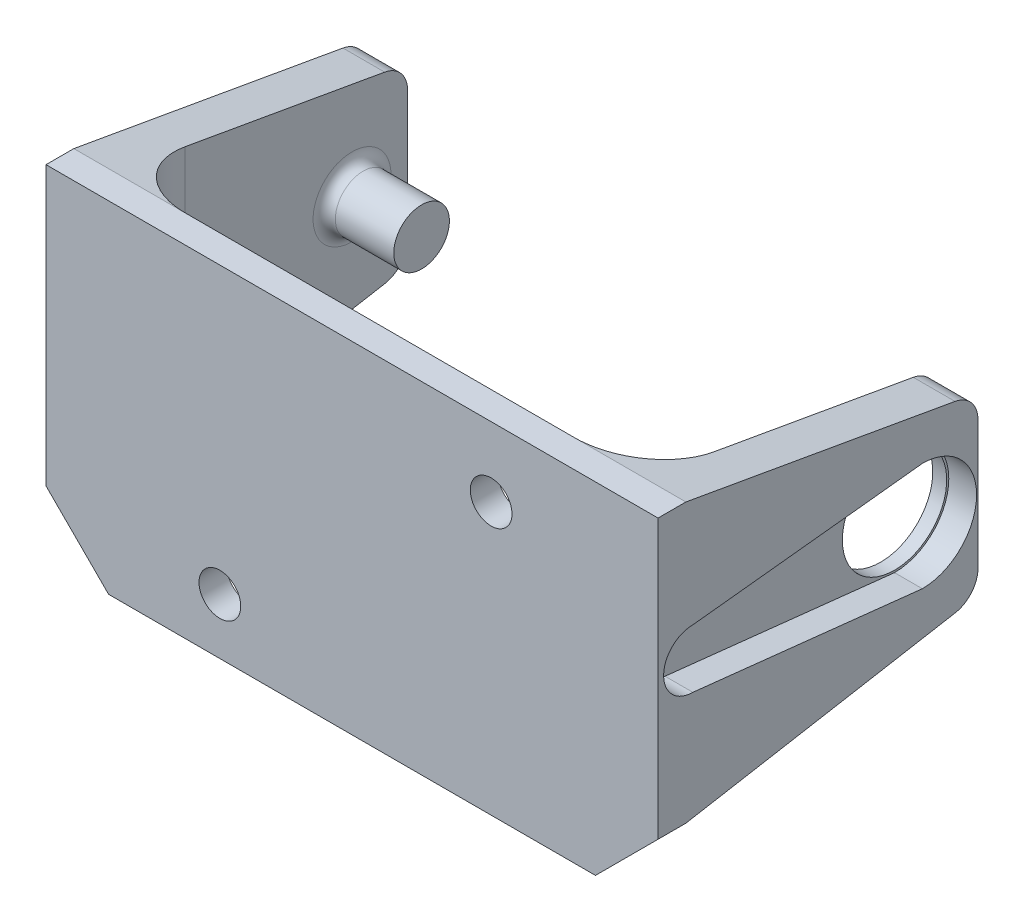
SolidWorks part; units mm, degrees
ref_plane "Front Plane" through (0, 0, 0) normal (0, 0, 1) x (1, 0, 0)
ref_plane "Top Plane" through (0, 0, 0) normal (0, 1, 0) x (1, 0, 0)
ref_plane "Right Plane" through (0, 0, 0) normal (1, 0, 0) x (0, 0, -1)
sketch "Sketch1" plane through (0, 0, 0) normal (0, 0, 1) x (1, 0, 0)
  line L1 (-19, -10) -> (19, -10)
  line L2 (-19, -10) -> (-19, 10)
  line L3 (-19, 10) -> (19, 10)
  line L4 (19, -10) -> (19, 10)
  line L5 (-19, -10) -> (19, 10) construction
  line L6 (-19, 10) -> (19, -10) construction
  point P0 (0, 0)
  dimension "D1" = 38
  dimension "D2" = 20
extrude "Boss-Extrude1" add sketch "Sketch1" along normal blind 2
sketch "Sketch2" plane through (19, 0, 0) normal (1, 0, 0) x (0, 0, -1)
  line L0 (-2, 10) -> (0, 10)
  line L1 (0, 10) -> (19.3473, 6.5885)
  line L2 (21, 4.6189) -> (21, -4.6189)
  line L3 (19.3473, -6.5885) -> (0, -10)
  line L4 (0, -10) -> (-2, -10)
  line L5 (-2, -10) -> (-2, 10)
  arc A0 (21, -4.6189) -> (19.3473, -6.5885) centre (19, -4.6189) cw
  arc A1 (19.3473, 6.5885) -> (21, 4.6189) centre (19, 4.6189) cw
  point P12 (21, -6.2971)
  dimension "D4" = 2
  dimension "D1" = 100
  dimension "D2" = 100
  dimension "D3" = 21
extrude "Boss-Extrude2" add sketch "Sketch2" along normal blind 3
mirror "Mirror1" about plane through (0, 0, 0) normal (1, 0, 0) of "Boss-Extrude2"
sketch "Sketch3" plane through (0, 0, 0) normal (0, 0, -1) x (-1, 0, 0)
  line L0 (-22, -10) -> (-17.5, -14.5)
  line L1 (-17.5, -14.5) -> (17.5, -14.5)
  line L2 (17.5, -14.5) -> (22, -10)
  line L3 (22, -10) -> (-22, -10)
  line L4 (-22, 10) -> (22, 10)
  line L5 (22, 10) -> (17.5, 14.5)
  line L6 (17.5, 14.5) -> (-17.5, 14.5)
  line L7 (-17.5, 14.5) -> (-22, 10)
  dimension "D1" = 45
  dimension "D2" = 45
  dimension "D3" = 45
  dimension "D4" = 45
  dimension "D5" = 35
  dimension "D6" = 35
extrude "Boss-Extrude3" add sketch "Sketch3" against normal blind 2
sketch "Sketch4" plane through (-22, 0, 0) normal (-1, 0, 0) x (0, 0, 1)
  line L0 (-21, -4.6189) -> (-21, 4.6189) construction
  circle A0 centre (-17, 0) radius 4
  circle A1 centre (-17, 0) radius 1.3
  dimension "D1" = 8
  dimension "D2" = 2.6
extrude "Cut-Extrude1" cut sketch "Sketch4" against normal through all contours A1
sketch "Sketch5" plane through (19, 0, 0) normal (-1, 0, 0) x (0, 0, 1)
  line L16 (-0.5, -2.1) -> (-17, -3.9)
  line L17 (-17, 3.9) -> (-0.5, 2.1)
  arc A2 (-17, 3.9) -> (-17, -3.9) centre (-17, 0) ccw
  arc A3 (-0.5, -2.1) -> (-0.5, 2.1) centre (-0.5, 0) ccw
  dimension "D1" = 7.8
  dimension "D2" = 4.2
  dimension "D3" = 16.5
extrude "Cut-Extrude2" cut sketch "Sketch5" against normal blind 2 from offset 1 offset against normal yes
sketch "Sketch6" plane through (19, 0, 0) normal (-1, 0, 0) x (0, 0, 1)
  circle A1 centre (-17, 0) radius 1.3 construction
  circle A2 centre (-17, 0) radius 3.75
  dimension "D1" = 7.5
extrude "Cut-Extrude3" cut sketch "Sketch6" against normal blind 2.4
sketch "Sketch7" plane through (0, 0, 0) normal (0, 0, -1) x (-1, 0, 0)
  line L1 (22, 10) -> (-22, 10)
  line L2 (22, 10) -> (22, 16)
  line L3 (22, 16) -> (-22, 16)
  line L4 (-22, 10) -> (-22, 16)
  dimension "D1" = 6
extrude "Cut-Extrude4" cut sketch "Sketch7" against normal through all
sketch "Sketch8" plane through (-22, 0, 0) normal (-1, 0, 0) x (0, 0, 1)
  circle A0 centre (-17, 0) radius 2
  dimension "D1" = 4
extrude "Boss-Extrude4" add sketch "Sketch8" against normal blind 8
fillet "Fillet1" radius 0.8 1 edges at (-19, 0, -19)
fillet "Fillet2" radius 5 2 edges
sketch "Sketch9" plane through (0, 0, 0) normal (0, 0, -1) x (-1, 0, 0)
  line L0 (-14, 10) -> (14, 10) construction
  line L1 (-22, -4.6189) -> (-22, 4.6189) construction
  line L2 (-17.5, -14.5) -> (17.5, -14.5) construction
  circle A0 centre (-10, 5) radius 1.5
  circle A1 centre (9.5, -10.5) radius 1.5
  dimension "D1" = 3
  dimension "D2" = 3
  dimension "D3" = 5
  dimension "D4" = 12
  dimension "D5" = 8
  dimension "D6" = 4
extrude "Cut-Extrude5" cut sketch "Sketch9" against normal blind 10
